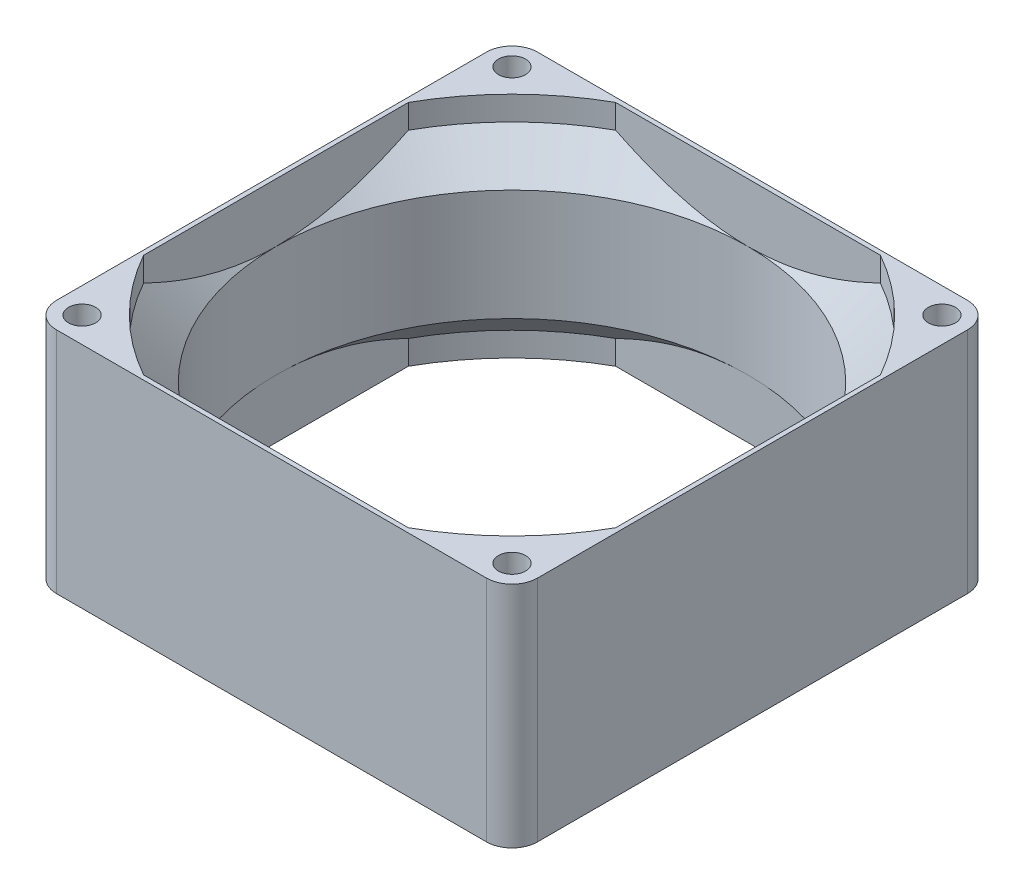
SolidWorks part; units mm, degrees
ref_plane "Front Plane" through (0, 0, 0) normal (0, 0, 1) x (1, 0, 0)
ref_plane "Top Plane" through (0, 0, 0) normal (0, 1, 0) x (1, 0, 0)
ref_plane "Right Plane" through (0, 0, 0) normal (1, 0, 0) x (0, 0, -1)
sketch "Sketch1" plane through (0, 0, 0) normal (0, 1, 0) x (1, 0, 0)
  line L0 (22.0099, 39.25) -> (-22.0099, 39.25)
  line L1 (-35.75, -40) -> (35.75, -40)
  line L2 (-40, -35.75) -> (-40, 35.75)
  line L3 (-35.75, 40) -> (35.75, 40)
  line L4 (40, -35.75) -> (40, 35.75)
  line L5 (-40, -40) -> (40, 40) construction
  line L6 (-40, 40) -> (40, -40) construction
  line L7 (39.25, -22.0099) -> (39.25, 22.0099)
  line L8 (-22.0099, -39.25) -> (22.0099, -39.25)
  line L9 (-39.25, 22.0099) -> (-39.25, -22.0099)
  arc A0 (22.0099, 39.25) -> (39.25, 22.0099) centre (0, 0) cw
  arc A1 (39.25, -22.0099) -> (22.0099, -39.25) centre (0, 0) cw
  arc A2 (-22.0099, -39.25) -> (-39.25, -22.0099) centre (0, 0) cw
  arc A3 (-39.25, 22.0099) -> (-22.0099, 39.25) centre (0, 0) cw
  circle A4 centre (35.75, 35.75) radius 2.25
  circle A5 centre (35.75, -35.75) radius 2.25
  circle A6 centre (-35.75, -35.75) radius 2.25
  circle A7 centre (-35.75, 35.75) radius 2.25
  arc A8 (-35.75, -40) -> (-40, -35.75) centre (-35.75, -35.75) cw
  arc A9 (35.75, -40) -> (40, -35.75) centre (35.75, -35.75) ccw
  arc A10 (35.75, 40) -> (40, 35.75) centre (35.75, 35.75) cw
  arc A11 (-40, 35.75) -> (-35.75, 40) centre (-35.75, 35.75) cw
  point P0 (0, 0)
  point P22 (0, 0)
  point P27 (0, 0)
  dimension "D2" = 45
  dimension "D5" = 4.5
  dimension "D1" = 80
  dimension "D3" = 39.25
  dimension "D7" = 71.5
  dimension "D4" = 4
  dimension "D6" = 4
extrude "Boss-Extrude1" add sketch "Sketch1" along normal blind 38
sketch "Sketch2" plane through (0, 0, 0) normal (1, 0, 0) x (0, 0, -1)
  line L0 (0, 0) -> (0, 29.5169) construction
  line L1 (39.25, 28.25) -> (45, 34)
  line L2 (39.25, 38) -> (39.25, 0) construction
  line L3 (39.25, 28.25) -> (39.25, 9.75)
  line L4 (45, 34) -> (45, 4)
  line L5 (45, 4) -> (39.25, 9.75)
  line L6 (-35.75, 38) -> (35.75, 38) construction
  line L7 (-35.75, 0) -> (35.75, 0) construction
  line L8 (-35.75, 38) -> (35.75, 38)
  line L9 (-35.75, 0) -> (35.75, 0)
  line L10 (39.25, 19) -> (45, 19) construction
  dimension "D1" = 45
  dimension "D2" = 4
  dimension "D3" = 45
revolve "Revolve1" add sketch "Sketch2" angle 360 about L0
sketch "Sketch3" plane through (0, 0, 0) normal (0, 1, 0) x (1, 0, 0)
  line L0 (-40, 35.75) -> (-40, -35.75) construction
  line L1 (-40, 35.75) -> (-40, -35.75)
  line L2 (-35.75, -40) -> (35.75, -40) construction
  line L3 (40, -35.75) -> (40, 35.75) construction
  line L4 (35.75, 40) -> (-35.75, 40) construction
  line L5 (-35.75, -40) -> (35.75, -40)
  line L6 (40, -35.75) -> (40, 35.75)
  line L7 (35.75, 40) -> (-35.75, 40)
  arc A0 (-40, -35.75) -> (-35.75, -40) centre (-35.75, -35.75) ccw construction
  arc A1 (35.75, -40) -> (40, -35.75) centre (35.75, -35.75) ccw construction
  arc A2 (40, 35.75) -> (35.75, 40) centre (35.75, 35.75) ccw construction
  arc A3 (-40, -35.75) -> (-35.75, -40) centre (-35.75, -35.75) ccw
  arc A4 (35.75, -40) -> (40, -35.75) centre (35.75, -35.75) ccw
  arc A5 (40, 35.75) -> (35.75, 40) centre (35.75, 35.75) ccw
  arc A6 (-35.75, 40) -> (-40, 35.75) centre (-35.75, 35.75) ccw construction
  arc A7 (-35.75, 40) -> (-40, 35.75) centre (-35.75, 35.75) ccw
  circle A8 centre (0, 0) radius 54.8081
extrude "Cut-Extrude1" cut sketch "Sketch3" against normal through all both and the other way through all contours A7 A8 A3 L1 | A3 A8 A4 L5 | A4 A8 A5 L6 | A5 A8 A7 L7
